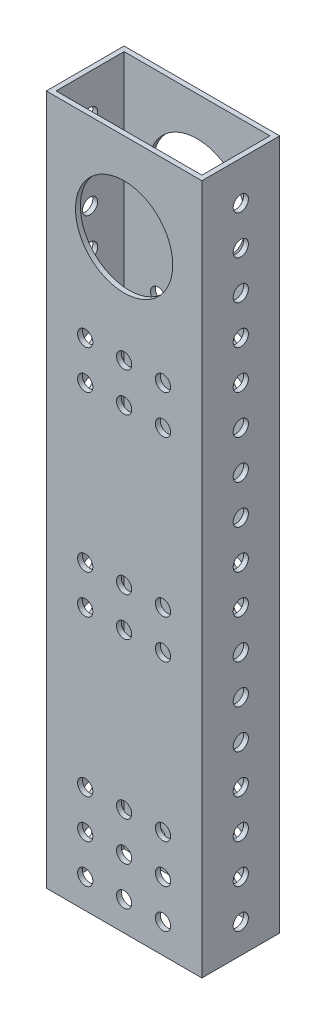
SolidWorks part; units mm, degrees
material "6061-T6 (SS)"
ref_plane "Front Plane" through (0, 0, 0) normal (0, 0, 1) x (1, 0, 0)
ref_plane "Top Plane" through (0, 0, 0) normal (0, 1, 0) x (1, 0, 0)
ref_plane "Right Plane" through (0, 0, 0) normal (1, 0, 0) x (0, 0, -1)
sketch "Sketch1" plane through (0, 0, 0) normal (0, 0, 1) x (1, 0, 0)
  line L0 (25.4, 225.425) -> (25.4, 0) construction
  line L1 (0, 0) -> (50.8, 0)
  line L2 (0, 0) -> (0, 225.425)
  line L3 (0, 225.425) -> (50.8, 225.425)
  line L4 (50.8, 0) -> (50.8, 225.425)
  line L5 (50.8, 9.525) -> (0, 9.525) construction
  circle A0 centre (25.4, 196.85) radius 15.875
  circle A1 centre (25.4, 9.525) radius 2.4892
  circle A2 centre (38.1, 9.525) radius 2.4892
  circle A3 centre (12.7, 9.525) radius 2.4892
  circle A4 centre (12.7, 22.225) radius 2.4892
  circle A5 centre (25.4, 22.225) radius 2.4892
  circle A6 centre (38.1, 22.225) radius 2.4892
  circle A7 centre (12.7, 34.925) radius 2.4892
  circle A8 centre (25.4, 34.925) radius 2.4892
  circle A9 centre (38.1, 34.925) radius 2.4892
  circle A19 centre (12.7, 85.725) radius 2.4892
  circle A20 centre (25.4, 85.725) radius 2.4892
  circle A21 centre (38.1, 85.725) radius 2.4892
  circle A22 centre (12.7, 98.425) radius 2.4892
  circle A23 centre (25.4, 98.425) radius 2.4892
  circle A24 centre (38.1, 98.425) radius 2.4892
  circle A34 centre (12.7, 149.225) radius 2.4892
  circle A35 centre (25.4, 149.225) radius 2.4892
  circle A36 centre (38.1, 149.225) radius 2.4892
  circle A37 centre (12.7, 161.925) radius 2.4892
  circle A38 centre (25.4, 161.925) radius 2.4892
  circle A39 centre (38.1, 161.925) radius 2.4892
  circle A40 centre (38.1, 47.625) radius 2.4892 [skipped]
  circle A41 centre (25.4, 47.625) radius 2.4892 [skipped]
  circle A42 centre (12.7, 47.625) radius 2.4892 [skipped]
  circle A43 centre (12.7, 60.325) radius 2.4892 [skipped]
  circle A44 centre (25.4, 60.325) radius 2.4892 [skipped]
  circle A45 centre (38.1, 60.325) radius 2.4892 [skipped]
  circle A46 centre (38.1, 73.025) radius 2.4892 [skipped]
  circle A47 centre (25.4, 73.025) radius 2.4892 [skipped]
  circle A48 centre (12.7, 73.025) radius 2.4892 [skipped]
  circle A49 centre (12.7, 123.825) radius 2.4892 [skipped]
  circle A50 centre (12.7, 136.525) radius 2.4892 [skipped]
  circle A51 centre (38.1, 136.525) radius 2.4892 [skipped]
  circle A52 centre (38.1, 123.825) radius 2.4892 [skipped]
  circle A53 centre (12.7, 111.125) radius 2.4892 [skipped]
  circle A54 centre (38.1, 111.125) radius 2.4892 [skipped]
  circle A55 centre (25.4, 136.525) radius 2.4892 [skipped]
  circle A56 centre (25.4, 123.825) radius 2.4892 [skipped]
  circle A57 centre (25.4, 111.125) radius 2.4892 [skipped]
  dimension "D3" = 31.75
  dimension "D5" = 4.9784
  dimension "D1" = 50.8
  dimension "D2" = 225.425
  dimension "D4" = 196.85
  dimension "D6" = 9.525
  dimension "D7" = 12.7
  dimension "D8" = 12.7
  dimension "D10" = 12.7
  dimension "D9" = 13
extrude "Boss-Extrude1" add sketch "Sketch1" along normal blind 25.4
sketch "Sketch2" plane through (50.8, 0, 0) normal (1, 0, 0) x (0, 0, -1)
  line L0 (-12.7, 0) -> (-12.7, 225.425) construction
  line L1 (-25.4, 0) -> (0, 0) construction
  line L2 (-25.4, 225.425) -> (0, 225.425) construction
  circle A0 centre (-12.7, 9.525) radius 2.4892
  circle A1 centre (-12.7, 22.225) radius 2.4892
  circle A2 centre (-12.7, 34.925) radius 2.4892
  circle A3 centre (-12.7, 47.625) radius 2.4892
  circle A4 centre (-12.7, 60.325) radius 2.4892
  circle A5 centre (-12.7, 73.025) radius 2.4892
  circle A6 centre (-12.7, 85.725) radius 2.4892
  circle A7 centre (-12.7, 98.425) radius 2.4892
  circle A8 centre (-12.7, 111.125) radius 2.4892
  circle A9 centre (-12.7, 123.825) radius 2.4892
  circle A10 centre (-12.7, 136.525) radius 2.4892
  circle A11 centre (-12.7, 149.225) radius 2.4892
  circle A12 centre (-12.7, 161.925) radius 2.4892
  circle A13 centre (-12.7, 174.625) radius 2.4892
  circle A14 centre (-12.7, 187.325) radius 2.4892
  circle A15 centre (-12.7, 200.025) radius 2.4892
  circle A16 centre (-12.7, 212.725) radius 2.4892
  dimension "D2" = 4.9784
  dimension "D1" = 9.525
  dimension "D4" = 12.7
  dimension "D3" = 17
extrude "Cut-Extrude1" cut sketch "Sketch2" against normal through all
sketch "Sketch3" plane through (0, 225.425, 0) normal (0, 1, 0) x (1, 0, 0)
  line L8 (49.2125, -1.5875) -> (1.5875, -1.5875)
  line L9 (1.5875, -1.5875) -> (1.5875, -23.8125)
  line L10 (1.5875, -23.8125) -> (49.2125, -23.8125)
  line L11 (49.2125, -23.8125) -> (49.2125, -1.5875)
  line L12 (49.2125, -1.5875) -> (1.5875, -1.5875)
  line L13 (1.5875, -1.5875) -> (1.5875, -23.8125)
  line L14 (1.5875, -23.8125) -> (49.2125, -23.8125)
  line L15 (49.2125, -23.8125) -> (49.2125, -1.5875)
  dimension "D1" = 1.5875
extrude "Cut-Extrude2" cut sketch "Sketch3" against normal through all
